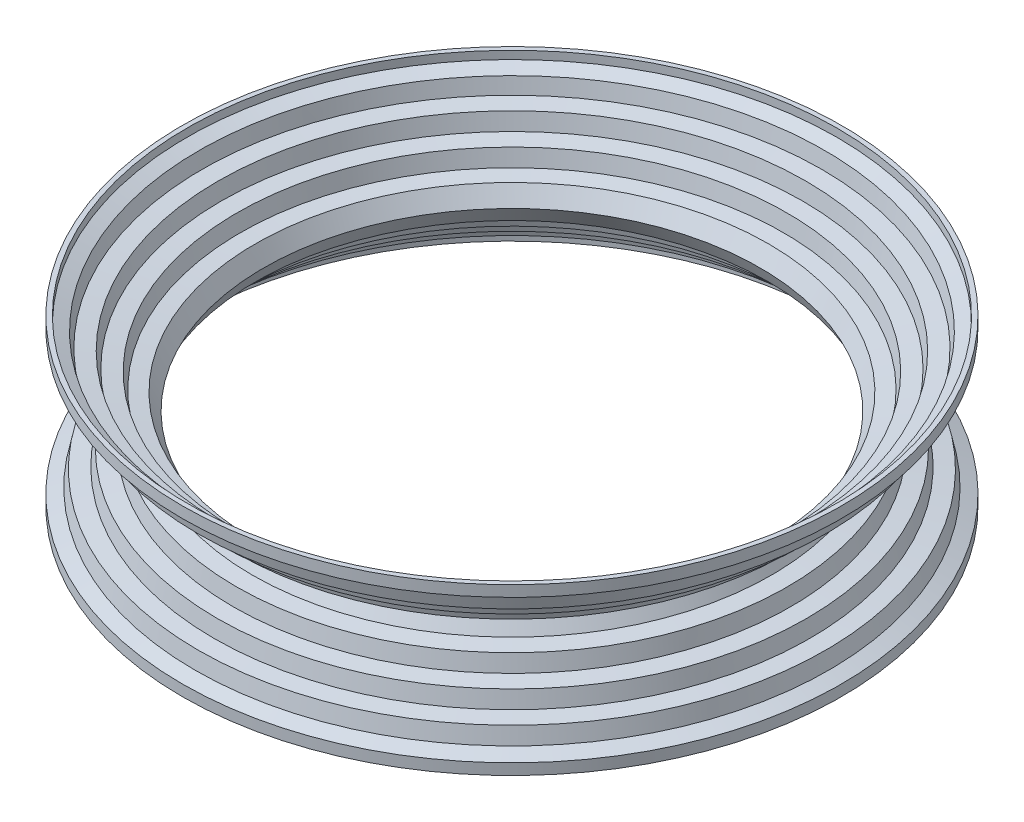
SolidWorks part; units mm, degrees
ref_plane "정면" through (0, 0, 0) normal (0, 0, 1) x (1, 0, 0)
ref_plane "윗면" through (0, 0, 0) normal (0, 1, 0) x (1, 0, 0)
ref_plane "우측면" through (0, 0, 0) normal (1, 0, 0) x (0, 0, -1)
sketch "스케치1" plane through (0, 0, 0) normal (0, 1, 0) x (1, 0, 0)
  circle A7 centre (0, 0) radius 35.8938
  dimension "D2" = 71.7876
extrude "보스-돌출1" add sketch "스케치1" along normal blind 1.2
ref_plane "평면1" through (0, 9, 0) normal (0, -1, 0) x (-1, 0, 0)
sketch "스케치3" plane through (0, 9, 0) normal (0, -1, 0) x (-1, 0, 0)
  circle A0 centre (0, 0) radius 27.5887
  dimension "D1" = 55.1775
sketch "스케치4" plane through (0, 0, 0) normal (1, 0, 0) x (0, 0, -1)
  line L0 (-33.8164, 3.1511) -> (-34.1587, 3.5156) construction
  line L1 (-27.5887, 9) -> (27.5887, 9) construction
  line L2 (0, 9) -> (0, 1.2) construction
  line L3 (35.8938, 1.2) -> (-35.8938, 1.2) construction
  line L4 (-35.8938, 1.2) -> (-36.2361, 1.5645) construction
  line L5 (-31.7389, 5.1022) -> (-32.0812, 5.4667) construction
  line L6 (-29.6615, 7.0533) -> (-30.0038, 7.4178) construction
  line L7 (-27.5841, 9.0044) -> (-27.9264, 9.3688) construction
  line L8 (0, 9) -> (-27.5887, 9) construction
  line L9 (-35.8938, 1.2) -> (-33.8164, 3.1511) construction
  line L10 (-31.7413, 5.1) -> (-35.8938, 1.2) construction
  line L11 (-31.7413, 5.1) -> (-27.5887, 9) construction
  line L12 (-34.8551, 2.1755) -> (-34.5128, 1.8111) construction
  line L13 (0, 9) -> (27.5887, 9) construction
  line L14 (-27.5887, 9) -> (0, 9)
  line L15 (0, 9) -> (0, 1.2)
  line L16 (-35.8938, 1.2) -> (0, 1.2)
  line L17 (-32.7777, 4.1266) -> (-32.4354, 3.7622) construction
  line L18 (-30.7002, 6.0777) -> (-30.3579, 5.7133) construction
  line L19 (-28.6228, 8.0288) -> (-28.2805, 7.6644) construction
  line L20 (-34.8551, 2.1755) -> (-32.7777, 4.1266) construction
  line L21 (-35.8938, 1.2) -> (-34.5128, 1.8111)
  line L22 (-34.5128, 1.8111) -> (-34.1587, 3.5156)
  line L23 (-34.1587, 3.5156) -> (-32.4354, 3.7622)
  line L24 (-32.4354, 3.7622) -> (-32.0812, 5.4667)
  line L25 (-32.0812, 5.4667) -> (-30.3579, 5.7133)
  line L26 (-30.3579, 5.7133) -> (-30.0038, 7.4178)
  line L27 (-30.0038, 7.4178) -> (-28.2805, 7.6644)
  line L28 (-28.2805, 7.6644) -> (-27.5841, 9.0044)
  point P25 (-28.2805, 7.6644)
  dimension "D1" = 55.1775
  dimension "D2" = 5
  dimension "D3" = 2.85
  dimension "D4" = 0.5
  dimension "D5" = 2.85
revolve "회전2" add sketch "스케치4" angle 360 about L2
mirror "대칭 복사1" about plane through (0, 9, 0) normal (0, -1, 0) of "보스-돌출1", "회전2"
shell "쉘1" thickness 0.5
